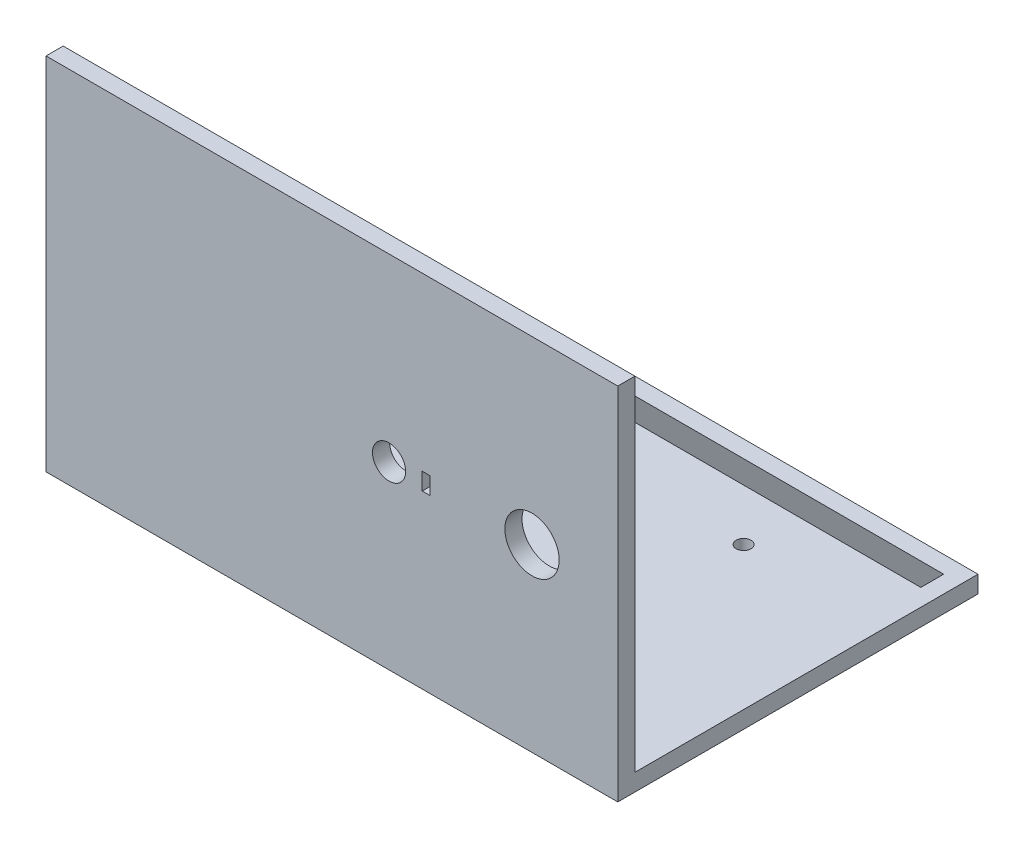
SolidWorks part; units mm, degrees
ref_plane "Front Plane" through (0, 0, 0) normal (0, 0, 1) x (1, 0, 0)
ref_plane "Top Plane" through (0, 0, 0) normal (0, 1, 0) x (1, 0, 0)
ref_plane "Right Plane" through (0, 0, 0) normal (1, 0, 0) x (0, 0, -1)
sketch "Sketch1" plane through (0, 0, 0) normal (0, 1, 0) x (1, 0, 0)
  line L1 (-63.5, 40.005) -> (63.5, 40.005)
  line L2 (-63.5, 40.005) -> (-63.5, -40.005)
  line L3 (-63.5, -40.005) -> (63.5, -40.005)
  line L4 (63.5, 40.005) -> (63.5, -40.005)
  line L5 (-63.5, 40.005) -> (63.5, -40.005) construction
  line L6 (-63.5, -40.005) -> (63.5, 40.005) construction
  point P0 (0, 0)
  dimension "D1" = 80.01
  dimension "D2" = 127
extrude "Base" add sketch "Sketch1" along normal blind 3.81 contours L2 L3 L4 L1
sketch "Sketch2" plane through (0, 3.81, 0) normal (0, 1, 0) x (1, 0, 0)
  line L0 (63.5, 40.005) -> (63.5, -40.005) construction
  line L1 (-63.5, -40.005) -> (63.5, -40.005)
  line L2 (-63.5, -40.005) -> (-63.5, -36.195)
  line L3 (-63.5, -36.195) -> (63.5, -36.195)
  line L4 (63.5, -40.005) -> (63.5, -36.195)
  line L5 (-63.5, -40.005) -> (63.5, -40.005) construction
  dimension "D1" = 3.81
extrude "Front Paneling" add sketch "Sketch2" along normal blind 76.2
sketch "Sketch4" plane through (0, 3.81, 0) normal (0, 1, 0) x (1, 0, 0)
  line L0 (-63.5, 40.005) -> (-63.5, -36.195) construction
  line L1 (63.5, -36.195) -> (-63.5, -36.195) construction
  circle A0 centre (-44.45, -28.575) radius 1.651
  circle A1 centre (-43.18, 19.685) radius 1.651
  circle A2 centre (31.75, 19.685) radius 1.651
  circle A3 centre (38.1, -28.575) radius 1.651
  point P12 (0, 0)
  point P13 (0, 0)
  dimension "D1" = 3.302
  dimension "D4" = 3.302
  dimension "D7" = 3.302
  dimension "D9" = 3.302
  dimension "D2" = 19.05
  dimension "D3" = 7.62
  dimension "D5" = 48.26
  dimension "D6" = 1.27
  dimension "D8" = 74.93
  dimension "D10" = 82.55
  dimension "D11" = 48.26
  dimension "D12" = 48.26
extrude "Arduino Mounting Holes" cut sketch "Sketch4" against normal through all
sketch3d "Plane for Strut" plane through (0, 0, 0) normal (0, 0, 1) x (1, 0, 0)
  dimension "D1" = 7.62
sketch "Sketch3" plane through (-55.88, 0, 0) normal (-1, 0, 0) x (0, 0, 1)
  line L0 (36.195, 76.2) -> (-36.195, 3.81)
  line L1 (36.195, 80.01) -> (36.195, 3.81) construction
  line L2 (-40.005, 3.81) -> (36.195, 3.81) construction
  line L3 (-36.195, 3.81) -> (-31.115, 3.81)
  line L4 (-31.115, 3.81) -> (36.195, 71.12)
  line L5 (36.195, 71.12) -> (36.195, 76.2)
  dimension "D1" = 3.81
  dimension "D2" = 3.81
  dimension "D3" = 5.08
extrude "Stability Strut" add sketch "Sketch3" along normal blind 3.81
mirror "Mirror Strut" about plane through (0, 0, 0) normal (1, 0, 0) of "Stability Strut"
sketch "Sketch5" plane through (0, 0, 40.005) normal (0, 0, 1) x (1, 0, 0)
  line L0 (-63.5, 40.005) -> (63.5, 40.005) construction
  line L1 (63.5, 80.01) -> (63.5, 0) construction
  circle A0 centre (44.45, 40.005) radius 6.0325
  point P4 (5.3108, 46.8774)
  point P5 (50.8, 27.305)
  dimension "D1" = 12.065
  dimension "D2" = 19.05
sketch "Hole/button Line" plane through (0, 0, 40.005) normal (0, 0, 1) x (1, 0, 0)
  line L0 (-63.5, 40.005) -> (63.5, 40.005) construction
  line L1 (-63.5, 80.01) -> (-63.5, 0) construction
  line L2 (63.5, 80.01) -> (63.5, 0) construction
extrude "On Off Switch Recess" cut sketch "Sketch5" against normal through all
sketch "Sketch7" plane through (0, 0, 40.005) normal (0, 0, 1) x (1, 0, 0)
  line L0 (-63.5, 40.005) -> (63.5, 40.005) construction
  line L1 (63.5, 80.01) -> (63.5, 0) construction
  line L3 (20.066, 41.91) -> (21.844, 41.91)
  line L4 (20.066, 41.91) -> (20.066, 38.1)
  line L5 (20.066, 38.1) -> (21.844, 38.1)
  line L6 (21.844, 41.91) -> (21.844, 38.1)
  line L7 (20.066, 41.91) -> (21.844, 38.1) construction
  line L8 (20.066, 38.1) -> (21.844, 41.91) construction
  circle A0 centre (12.7, 40.005) radius 3.683
  point P6 (20.955, 40.005)
  point P11 (0, 0)
  point P12 (0, 0)
  dimension "D1" = 7.366
  dimension "D2" = 50.8
  dimension "D3" = 3.81
  dimension "D4" = 1.778
  dimension "D5" = 7.366
extrude "Potentiometer Recess" cut sketch "Sketch7" against normal blind 3.81
sketch "LED Line" plane through (0, 0, 40.005) normal (0, 0, 1) x (1, 0, 0)
  line L0 (63.5, 59.055) -> (-63.5, 59.055) construction
  line L1 (63.5, 80.01) -> (63.5, 0) construction
  line L2 (-63.5, 80.01) -> (-63.5, 0) construction
  line L3 (-63.5, 40.005) -> (63.5, 40.005) construction
  dimension "D1" = 19.05
sketch "Sketch9" plane through (0, 0, 40.005) normal (0, 0, 1) x (1, 0, 0)
  line L0 (63.5, 59.055) -> (-63.5, 59.055) construction
  circle A0 centre (44.45, 59.055) radius 2.54
  point P4 (44.45, 59.055)
  dimension "D1" = 5.08
